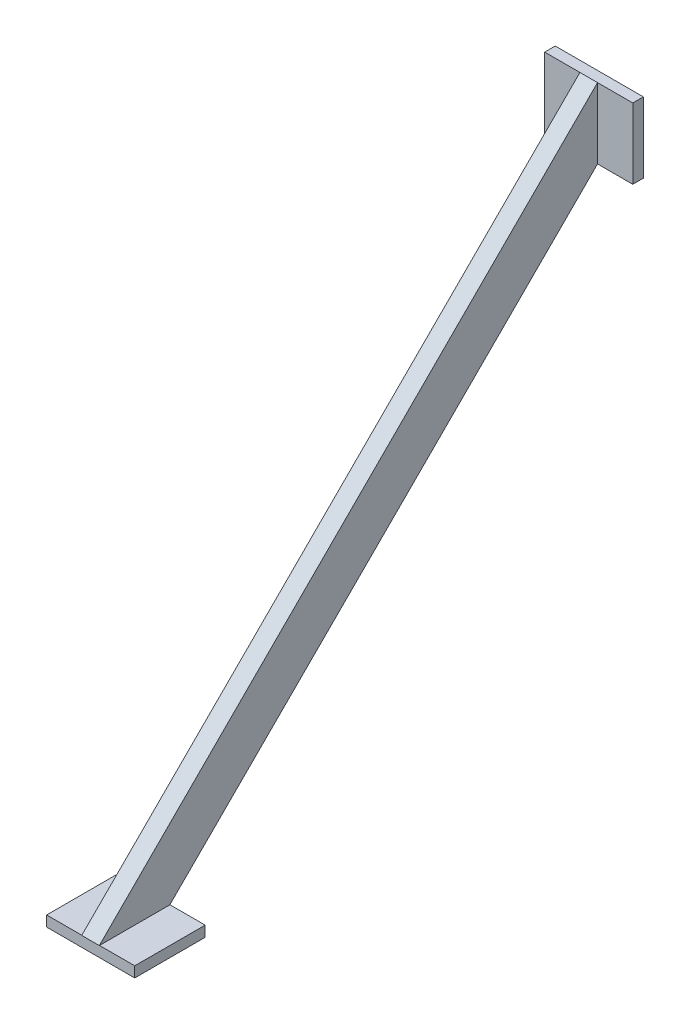
SolidWorks part; units mm, degrees
ref_plane "Front Plane" through (0, 0, 0) normal (0, 0, 1) x (1, 0, 0)
ref_plane "Top Plane" through (0, 0, 0) normal (0, 1, 0) x (1, 0, 0)
ref_plane "Right Plane" through (0, 0, 0) normal (1, 0, 0) x (0, 0, -1)
sketch "Sketch1" plane through (0, 0, 0) normal (1, 0, 0) x (0, 0, -1)
  line L0 (106.6647, 114.5121) -> (-34.7567, -26.9093)
  line L1 (-34.7567, -26.9093) -> (-14.7567, -26.9093)
  line L2 (-14.7567, -26.9093) -> (106.6647, 94.5121)
  line L3 (106.6647, 94.5121) -> (106.6647, 114.5121)
  dimension "D1" = 45
  dimension "D2" = 20
  dimension "D3" = 200
extrude "Boss-Extrude1" add sketch "Sketch1" along normal blind 5
sketch "Sketch2" plane through (0, -26.9093, 0) normal (0, -1, 0) x (1, 0, 0)
  line L0 (5, 14.7567) -> (5, -106.6647) construction
  line L1 (15, 34.7033) -> (-10, 34.7033)
  line L2 (15, 34.7033) -> (15, 14.7033)
  line L3 (15, 14.7033) -> (-10, 14.7033)
  line L4 (-10, 34.7033) -> (-10, 14.7033)
  dimension "D1" = 20
  dimension "D2" = 25
  dimension "D3" = 10
extrude "Boss-Extrude2" add sketch "Sketch2" along normal blind 3
sketch "Sketch3" plane through (0, 0, -106.6647) normal (0, 0, -1) x (-1, 0, 0)
  line L3 (8.7283, 94.5121) -> (10, 94.5121)
  line L4 (10, 114.5121) -> (10, 94.5121)
  line L6 (-15, 114.5121) -> (-15, 94.5121)
  line L7 (-15, 94.5121) -> (8.7283, 94.5121)
  line L8 (10, 114.5121) -> (-15, 114.5121)
  line L9 (0, 94.5121) -> (0, 114.5121) construction
  line L10 (-5, 114.5121) -> (0, 114.5121) construction
  dimension "D1" = 20
  dimension "D2" = 25
  dimension "D3" = 10
  dimension "D4" = 0
extrude "Boss-Extrude3" add sketch "Sketch3" along normal blind 3
